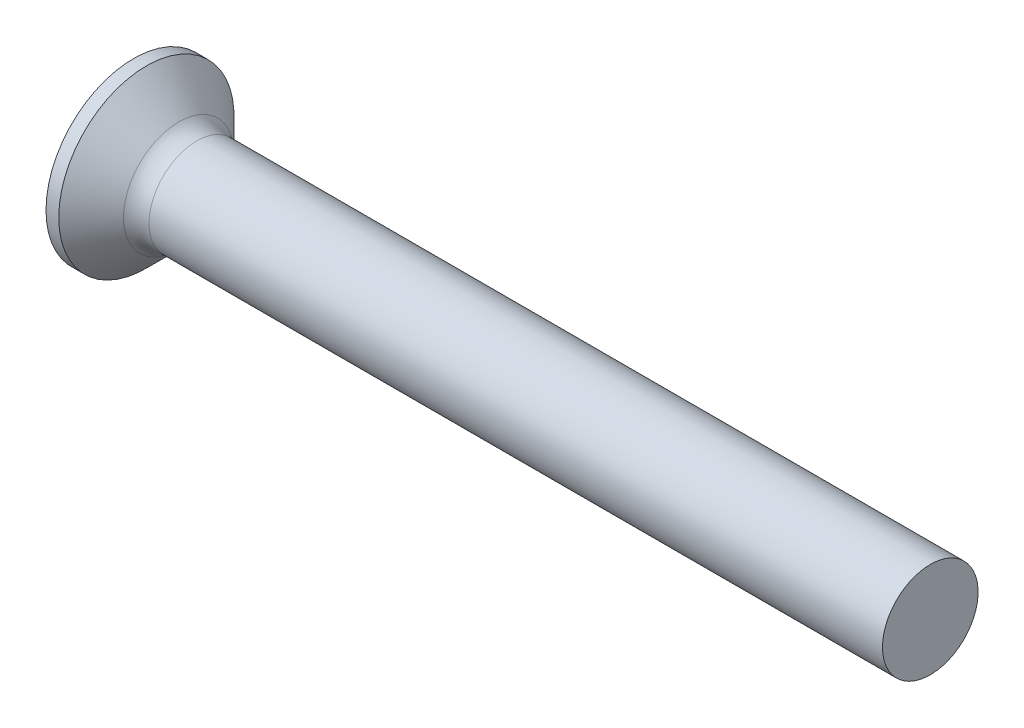
SolidWorks part; units mm, degrees
ref_plane "Plane1" through (0, 0, 0) normal (0, 0, 1) x (1, 0, 0)
ref_plane "Plane2" through (0, 0, 0) normal (0, 1, 0) x (1, 0, 0)
ref_plane "Plane3" through (0, 0, 0) normal (1, 0, 0) x (0, 0, -1)
sketch "BodySke" plane through (0, 0, 0) normal (0, 0, 1) x (1, 0, 0)
  line L0 (0, 0) -> (25.7, 0)
  line L1 (25.7, 0) -> (25.7, 1.5)
  line L2 (25.7, 1.5) -> (2.35, 1.5)
  line L3 (1.1, -2.75) -> (2.35, -1.5) construction
  line L4 (-15.875, 0) -> (82.55, 0) construction
  line L5 (1.1, 2.75) -> (2.35, 1.5)
  line L6 (2.85, 4.675) -> (2.85, -11.2) construction
  line L7 (0.7, 2.7793) -> (0.7, -13.0957) construction
  line L8 (1.1, 2.75) -> (0.7, 2.75)
  arc A0 (0, 0) -> (0.7, 2.75) centre (5.7518, 0) cw
  dimension "Head_ang" = 90
  dimension "Diameter" = 3
  dimension "Advance" = 0.5
  dimension "Thread_nom" = 25
  dimension "Oval_ht" = 0.7
  dimension "Side_ht" = 1.65
  dimension "Head_dia" = 5.5
  dimension "Length" = 25
revolve "Base-Revolve" add sketch "BodySke" angle 360 about L4
cosmetic thread "ThreadCosmetic" parameters "Thread_length"=22.85, "Thread_minor"=2.439
fillet "Fillet1" radius 0.8 1 edges at (2.35, 0, 1.5)
sketch "Sketch3" plane through (0, 0, 0) normal (1, 0, 0) x (0, 0, -1)
  line L0 (0.37, -1.55) -> (-0.37, -1.55)
  line L1 (0.37, -1.55) -> (0.37, 1.55)
  line L2 (-0.37, 1.55) -> (0.37, 1.55)
  line L3 (-0.37, 1.55) -> (-0.37, -1.55)
  dimension "Cross_width" = 0.74
  dimension "D1" = 0.37
  dimension "Cross_dia" = 3.1
  dimension "D2" = 1.55
ref_plane "Plane4" through (2.08, 0, 0) normal (1, 0, 0) x (0, 0, -1)
sketch "Sketch4" plane through (2.08, 0, 0) normal (1, 0, 0) x (0, 0, -1)
  line L0 (0.37, -0.513) -> (-0.37, -0.513)
  line L1 (0.37, -0.513) -> (0.37, 0.513)
  line L2 (-0.37, 0.513) -> (0.37, 0.513)
  line L3 (-0.37, 0.513) -> (-0.37, -0.513)
  dimension "D1" = 0.74
  dimension "D2" = 1.0259
  dimension "D3" = 0.37
  dimension "D4" = 0.513
loft "Recess" cut profiles "Sketch3", "Sketch4"
pattern_circular "RecPat" count 2 every 90 about axis through (0, 0, 0) along (1, 0, 0) of "Recess"
sketch "RecCorSke" plane through (0, 0, 0) normal (0, 0, 1) x (1, 0, 0)
  line L0 (-3.175, 0) -> (15.875, 0) construction
  line L2 (0, 0) -> (0, 0.7014)
  line L3 (0, 0.7014) -> (2.08, 0.556)
  line L4 (2.08, 0.556) -> (2.2607, 0)
  line L5 (2.2607, 0) -> (0, 0)
  dimension "Diameter" = 1.112
  dimension "Depth" = 2.08
  dimension "Draft_angle" = 4
  dimension "Bottom_angle" = 18
revolve "RecessCore" cut sketch "RecCorSke" angle 360 about L0
sketch "ThdSchSke" plane through (0, 0, 0) normal (0, 0, 1) x (1, 0, 0)
  line L0 (2.85, -1.2195) -> (2.6536, -1.5)
  line L1 (2.85, -1.2195) -> (3.0464, -1.5)
  line L2 (3.0464, -1.5) -> (3.0464, -1.875)
  line L3 (-3.175, 0) -> (5.1513, 0) construction
  line L5 (3.0464, -1.875) -> (2.6536, -1.875)
  line L6 (2.6536, -1.875) -> (2.6536, -1.5)
  dimension "Diameter" = 3
  dimension "SideAngle" = 55
  dimension "VeeAngle" = 70
  dimension "Thread_minor" = 2.439
  dimension "Overcut" = 3.75
  dimension "Start" = 2.85
revolve "ThreadSchematic" [suppressed] cut sketch "ThdSchSke" angle 360 about L3
pattern_linear "ThdSchPat" [suppressed]
equation "\"D1@Sketch3\" = \"Cross_width@Sketch3\" / 2"
equation "\"D2@Sketch3\" = \"Cross_dia@Sketch3\" / 2"
equation "\"Depth@RecCorSke\" = \"Cross_depth@Plane4\""
equation "\"D1@Sketch4\" = \"Cross_width@Sketch3\""
equation "\"D2@Sketch4\" = \"Cross_dia@Sketch3\" - 2.0 * \"Cross_depth@Plane4\" * tan(26.5  * 0.017453292)"
equation "\"D3@Sketch4\" = \"D1@Sketch4\" / 2"
equation "\"D4@Sketch4\" = \"D2@Sketch4\" / 2"
equation "\"Thread_length@ThreadCosmetic\" = ((sgn( (\"Length@BodySke\" - \"Advance@BodySke\" - \"Side_ht@BodySke\" ) - \"Thread_nom@BodySke\" )-1)*( (\"Length@BodySke\" - \"Advance@BodySke\" - \"Side_ht@BodySke\" ) - \"Thread_nom@BodySke\" ))/-2+ \"Thread_nom@BodySke\""
equation "\"Thread_minor@ThdSchSke\" = \"Thread_minor@ThreadCosmetic\""
equation "\"Diameter@ThdSchSke\" = \"Diameter@BodySke\""
equation "\"Overcut@ThdSchSke\" = \"Diameter@BodySke\" * 1.25"
equation "\"Start@ThdSchSke\" = \"Oval_ht@BodySke\" + \"Length@BodySke\" - \"Thread_length@ThreadCosmetic\"  '---Countersunk---"
equation "\"Num_threads@ThdSchPat\" = int( \"Thread_length@ThreadCosmetic\" / \"Advance@BodySke\" + 0.999 )  + 1"
equation "\"Advance@ThdSchPat\" = \"Thread_length@ThreadCosmetic\" /  (\"Num_threads@ThdSchPat\" - 1) 'relax it"
